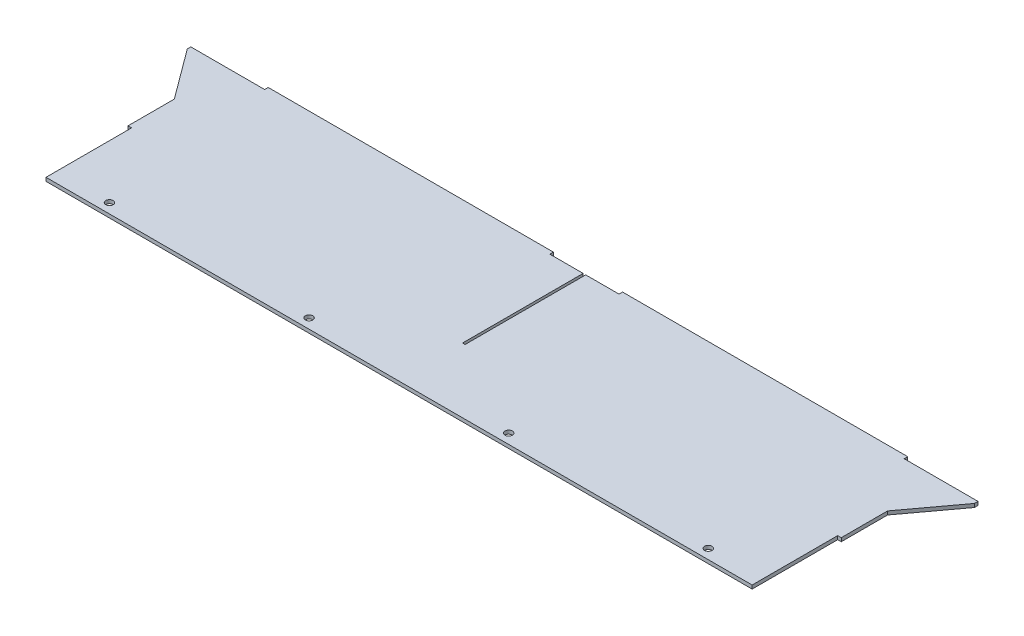
SolidWorks part; units mm, degrees
material "6061-T6 (SS)"
ref_plane "X-Y Datum" through (0, 0, 0) normal (0, 0, 1) x (1, 0, 0)
ref_plane "X-Z Datum" through (0, 0, 0) normal (0, 1, 0) x (1, 0, 0)
ref_plane "Y-Z Datum" through (0, 0, 0) normal (1, 0, 0) x (0, 0, -1)
sketch "Sketch1" plane through (0, 0, 0) normal (0, 1, 0) x (1, 0, 0)
  line L1 (-317.6778, 82.55) -> (317.6778, 82.55)
  line L2 (-317.6778, 82.55) -> (-317.6778, -82.55)
  line L3 (-317.6778, -82.55) -> (317.6778, -82.55)
  line L4 (317.6778, 82.55) -> (317.6778, -82.55)
  line L5 (-317.6778, 82.55) -> (317.6778, -82.55) construction
  line L6 (-317.6778, -82.55) -> (317.6778, 82.55) construction
  point P0 (0, 0)
  dimension "D1" = 635.3556
  dimension "D2" = 165.1
extrude "Boss-Extrude1" add sketch "Sketch1" along normal mid plane 3.175
sketch "Sketch2" plane through (0, 0, -82.55) normal (0, 0, -1) x (-1, 0, 0)
  line L20 (-317.6778, -1.5875) -> (317.6778, -1.5875) construction
  line L21 (-284.8229, -1.5875) -> (-30.8229, -1.5875)
  line L22 (30.8229, -1.5875) -> (284.8229, -1.5875)
  line L40 (30.8229, -1.5875) -> (30.8229, 1.5875)
  line L41 (30.8229, 1.5875) -> (284.8229, 1.5875)
  line L42 (284.8229, 1.5875) -> (284.8229, -1.5875)
  line L56 (-284.8229, -1.5875) -> (-284.8229, 1.5875)
  line L57 (-284.8229, 1.5875) -> (-30.8229, 1.5875)
  line L58 (-30.8229, 1.5875) -> (-30.8229, -1.5875)
extrude "Boss-Extrude2" add sketch "Sketch2" along normal blind 3.175
sketch "Sketch3" plane through (0, -1.5875, 0) normal (0, -1, 0) x (1, 0, 0)
  line L0 (317.6778, -82.55) -> (350.5784, -82.55)
  line L1 (350.5784, -82.55) -> (350.5784, -79.375)
  line L3 (350.5784, -79.375) -> (317.6778, -34.925)
  line L4 (317.6778, 82.55) -> (317.6778, -82.55) construction
  line L17 (317.6778, -82.55) -> (317.6778, 82.55)
  line L18 (317.6778, 82.55) -> (-317.6778, 82.55)
  line L19 (-317.6778, 82.55) -> (-317.6778, -82.55)
  line L20 (-317.6778, -82.55) -> (-284.8229, -82.55)
  line L21 (-284.8229, -82.55) -> (-284.8229, -85.725)
  line L22 (-284.8229, -85.725) -> (-30.8229, -85.725)
  line L23 (-30.8229, -85.725) -> (-30.8229, -82.55)
  line L24 (-30.8229, -82.55) -> (30.8229, -82.55)
  line L25 (30.8229, -82.55) -> (30.8229, -85.725)
  line L26 (30.8229, -85.725) -> (284.8229, -85.725)
  line L27 (284.8229, -85.725) -> (284.8229, -82.55)
  line L28 (284.8229, -82.55) -> (317.6778, -82.55)
  line L29 (317.6778, -82.55) -> (317.6778, -34.925)
  dimension "D1" = 32.9006
  dimension "D2" = 3.175
  dimension "D3" = 44.45
  dimension "D4" = 0
extrude "Boss-Extrude3" add sketch "Sketch3" against normal blind 3.175
mirror "Mirror1" about plane through (0, 0, 0) normal (1, 0, 0) of "Boss-Extrude3"
sketch "Sketch4" plane through (0, -1.5875, 0) normal (0, -1, 0) x (1, 0, 0)
  line L0 (-284.4038, 82.55) -> (-284.4038, 71.882)
  line L1 (-317.6778, 82.55) -> (317.6778, 82.55) construction
  line L2 (-284.4038, 71.882) -> (-317.6778, 71.882)
  line L3 (-317.6778, -34.925) -> (-317.6778, 82.55) construction
  circle A0 centre (-284.4038, 71.882) radius 3.675
extrude "Cut-Extrude1" [suppressed] cut sketch "Sketch4" against normal through all contours L2 A0 L0 | L0 A0 L2
pattern_linear "LPattern1" [suppressed] count 5 spacing 139.7
sketch "Sketch5" plane through (0, -1.5875, 0) normal (0, -1, 0) x (1, 0, 0)
  line L0 (-317.6778, 82.55) -> (317.6778, 82.55) construction
  line L1 (-317.6778, -34.925) -> (-317.6778, 82.55) construction
  line L2 (-317.6778, 82.55) -> (317.6778, 82.55)
  line L3 (-317.6778, -34.925) -> (-317.6778, 82.55)
  line L4 (0, 127.4245) -> (0, -127.4245) construction
  line L5 (-317.6778, 82.55) -> (-314.5028, 82.55)
  line L6 (-317.6778, 82.55) -> (-317.6778, 6.35)
  line L7 (-317.6778, 6.35) -> (-314.5028, 6.35)
  line L8 (-314.5028, 82.55) -> (-314.5028, 6.35)
  line L9 (317.6778, 6.35) -> (314.5028, 6.35)
  line L10 (314.5028, 82.55) -> (314.5028, 6.35)
  line L11 (317.6778, -34.925) -> (317.6778, 82.55)
  line L12 (30.8229, -82.55) -> (-30.8229, -82.55) construction
  line L13 (30.8229, -82.55) -> (-30.8229, -82.55)
  line L14 (-1.143, -85.725) -> (-1.143, -82.55) construction
  line L15 (-1.143, -85.725) -> (-1.143, -82.55)
  line L16 (-1.3081, -82.7151) -> (-1.3081, 25.0571)
  line L17 (-1.143, -82.55) -> (1.143, -82.55)
  line L18 (-1.143, -82.55) -> (-1.143, 24.892)
  line L19 (-1.143, 24.892) -> (1.143, 24.892)
  line L20 (1.143, -82.55) -> (1.143, 24.892)
  line L21 (-1.3081, 25.0571) -> (1.3081, 25.0571)
  line L22 (1.3081, -82.7151) -> (1.3081, 25.0571)
  line L23 (-1.3081, -82.7151) -> (1.3081, -82.7151)
  line L24 (-317.8048, 82.677) -> (-314.3758, 82.677)
  line L25 (-314.3758, 82.677) -> (-314.3758, 6.223)
  line L26 (-317.8048, 6.223) -> (-314.3758, 6.223)
  line L27 (-317.8048, 82.677) -> (-317.8048, 6.223)
  line L28 (314.3758, 82.55) -> (314.3758, 6.223)
  line L29 (317.6778, 6.223) -> (314.3758, 6.223)
  point P10 (0, 0)
  line M10 (317.6778, -34.925) -> (317.6778, 82.55)
  line M11 (317.6778, 82.55) -> (-317.6778, 82.55)
  line M12 (-317.6778, 82.55) -> (-317.6778, -34.925)
  dimension "D1" = 3.175
  dimension "D2" = 76.2
  dimension "D3" = 2.286
  dimension "D4" = 107.442
  dimension "D5" = 0.1651
  dimension "D6" = 0.127
extrude "Cut-Extrude2" cut sketch "Sketch5" against normal through all contours L19 L4 L17 L20 | L4 L19 L18 L13 | L8 L2 L7 M12 | L10 L9 M11 M10
sketch "Sketch6" plane through (0, -1.5875, 0) normal (0, -1, 0) x (1, 0, 0)
  line L0 (-314.5028, 82.55) -> (314.5028, 82.55) construction
  line L1 (-314.5028, 82.55) -> (314.5028, 82.55)
  line L2 (0, 127.6954) -> (0, 37.4046) construction
  circle A0 centre (266.7, 73.8124) radius 3
  point P6 (0, 82.55)
  dimension "D1" = 6
  dimension "D2" = 8.7376
hole_wizard "M6 Clearance Hole1" positions "Sketch7" profile "Sketch8" hole size "M6" standard "ANSI Metric" end condition through all
sketch "Sketch7" plane through (0, 1.5875, 0) normal (0, 1, 0) x (1, 0, 0)
  point P0 (266.7, -73.8124)
sketch "Sketch8" plane through (266.7, 1.5875, 73.8124) normal (1, 0, 0) x (0, 0, 1)
  line L0 (0, 0) -> (0, 3.175)
  line L1 (0, 3.175) -> (3.3, 3.175)
  line L2 (3.3, 3.175) -> (3.3, 0)
  line L5 (3.3, 0) -> (0, 0)
  line L11 (0, -6.35) -> (0, 107.95) construction
  dimension "Thru Hole Dia." = 6.6
  dimension "Thru Hole Depth" = 3.175
pattern_linear "LPattern2" count 4 spacing 177.8 along (-1, 0, 0) of "M6 Clearance Hole1"
